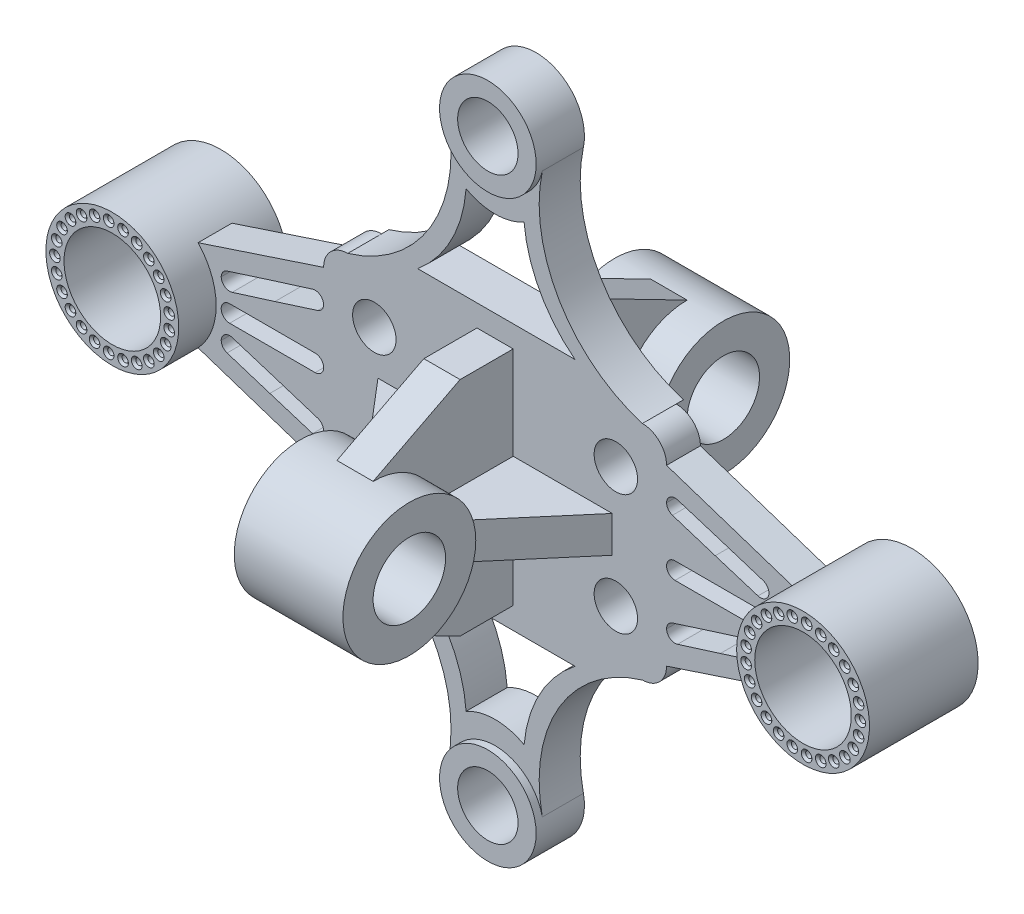
SolidWorks part; units mm, degrees
ref_plane "Front Plane" through (0, 0, 0) normal (1, 0, 0) x (0, 1, 0)
ref_plane "Top Plane" through (0, 0, 0) normal (0, 0, 1) x (0, 1, 0)
ref_plane "Right Plane" through (0, 0, 0) normal (0, 1, 0) x (-1, 0, 0)
sketch "Sketch1" plane through (0, 0, 0) normal (0, 0, 1) x (0, 1, 0)
  line L5 (-46, 71) -> (46, 71)
  line L6 (-46, 71) -> (-46, -71)
  line L7 (-46, -71) -> (46, -71)
  line L8 (46, 71) -> (46, -71)
  line L9 (-46, 71) -> (46, -71) construction
  line L10 (-46, -71) -> (46, 71) construction
  circle A1 centre (-25, -50) radius 9
  circle A2 centre (-25, 50) radius 9
  circle A3 centre (25, 50) radius 9
  circle A4 centre (25, -50) radius 9
  point P0 (0, 0)
  dimension "D5" = 18
  dimension "D1" = 92
  dimension "D2" = 142
  dimension "D3" = 21
  dimension "D4" = 21
  dimension "D6" = 2
  dimension "D7" = 2
extrude "Boss-Extrude1" add sketch "Sketch1" along normal blind 14
fillet "Fillet1" radius 10 4 edges at (-71, -46, 7) (-71, 46, 7) (71, 46, 7) (71, -46, 7)
sketch "Sketch2" plane through (0, 0, 0) normal (1, 0, 0) x (0, 1, 0)
  line L0 (-36, 0) -> (36, 0) construction
  circle A0 centre (0, 72) radius 27.5
  arc A1 (-27.5, 72) -> (27.5, 72) centre (0, 72) ccw
  point P6 (0, 0)
  point P7 (0, 0)
  dimension "D2" = 55
  dimension "D1" = 72
extrude "Boss-Extrude2" add sketch "Sketch2" along normal blind 22.5 and the other way blind 22.5 separate body contours A0
sketch "Sketch7" plane through (0, 0, 0) normal (1, 0, 0) x (0, 1, 0)
  line L0 (-46, 14) -> (-46, 36)
  line L1 (-36, 14) -> (-46, 14) construction
  line L2 (-46, 36) -> (-27.5, 72)
  line L3 (46, 14) -> (46, 36)
  line L4 (46, 36) -> (27.5, 72)
  line L5 (-46, 14) -> (46, 14)
  arc A0 (-27.5, 72) -> (27.5, 72) centre (0, 74.4278) ccw
  dimension "D2" = 27.607
  dimension "D1" = 22
extrude "Boss-Extrude3" add sketch "Sketch7" along normal blind 7.5 and the other way blind 7.5
sketch "Sketch8" plane through (0, 0, 0) normal (0, 1, 0) x (-1, 0, 0)
  line L0 (-22.5, 44.5) -> (-48.5, 14)
  line L1 (-61, 14) -> (-7.5, 14) construction
  dimension "D1" = 41
rib "Rib32" sketch "Sketch8" sketch "Sketch8" thickness 15 extrusion direction parallel to sketch draft on no parameters "D1"=15
mirror "Mirror1" about plane through (0, 0, 0) normal (1, 0, 0) of "Rib32"
sketch "Sketch9" plane through (22.5, 0, 0) normal (1, 0, 0) x (0, 1, 0)
  circle A0 centre (0, 72) radius 15
  dimension "D1" = 30
extrude "Cut-Extrude1" cut sketch "Sketch9" against normal through all
ref_plane "Plane1" through (0, 0, 7) normal (0, 0, 1) x (0, 1, 0)
mirror "Mirror3" about plane through (0, 0, 7) normal (0, 0, 1) of bodies 105
ref_plane "Plane3" through (0, 0, 7) normal (0, 0, 1) x (0, 1, 0)
sketch "Sketch11" plane through (0, 0, 7) normal (0, 0, 1) x (0, 1, 0)
  line L0 (36, 71) -> (-36, 71) construction
  line L1 (36, 71) -> (-36, 71)
  circle A0 centre (0, 143) radius 27.5
  circle A1 centre (0, 143) radius 20
  point P8 (0, 71)
  dimension "D2" = 55
  dimension "D3" = 40
  dimension "D1" = 72
extrude "Boss-Extrude4" add sketch "Sketch11" along normal blind 22.5 and the other way blind 22.5 separate body contours A0 | A1
sketch "Sketch12" plane through (0, 0, 7) normal (0, 0, 1) x (0, 1, 0)
  line L0 (-18.8482, 122.9751) -> (-36, 71)
  line L1 (36, 71) -> (18.8482, 122.9751)
  line L2 (36, 71) -> (-36, 71)
  circle A0 centre (0, 143) radius 27.5 construction
  arc A1 (18.8482, 122.9751) -> (-18.8482, 122.9751) centre (0, 143) cw
  dimension "D1" = 54.7321
extrude "Boss-Extrude5" add sketch "Sketch12" along normal blind 7 and the other way blind 7
hole_wizard "CSK for M2 Flat Head Machine Screw2" positions "Sketch17" profile "Sketch16" countersink size "M2" standard "ANSI Metric" end condition through all
sketch "Sketch17" plane through (0, 0, 29.5) normal (0, 0, 1) x (1, 0, 0)
  circle A0 centre (-143, 0) radius 27.5 construction
  point P0 (-166.75, 0)
  point P3 (0, 0)
  point P6 (0, 0)
  point P7 (0, 0)
  point P12 (-145.251, 5.2276)
  point P17 (-143.3311, -0.3544)
  dimension "D1" = 23.75
sketch "Sketch16" plane through (-166.75, 0, 29.5) normal (1, 0, 0) x (0, -1, 0)
  line L0 (0, 0) -> (0, 115)
  line L1 (0, 115) -> (1.3, 115)
  line L2 (1.3, 115) -> (1.3, 0.9)
  line L3 (1.3, 0.9) -> (2.2, 0)
  line L5 (2.2, 0) -> (0, 0)
  line L6 (-1.3, 0.9) -> (-2.2, 0) construction
  line L11 (0, -6.35) -> (0, 107.95) construction
  dimension "Thru Hole Dia." = 2.6
  dimension "Thru Hole Depth" = 115
  dimension "Near C'Sink Dia." = 4.4
  dimension "Near C'Sink Angle" = 90
pattern_circular "CirPattern1" count 25 over 360 about axis through (-143, 0, 0) along (0, 0, 1) of "CSK for M2 Flat Head Machine Screw2"
sketch "Sketch18" plane through (0, 0, 14) normal (0, 0, 1) x (1, 0, 0)
  line L0 (-109.9084, 11.449) -> (-74.5, 22.551) construction
  line L1 (-110.9555, 14.7887) -> (-75.5471, 25.8906)
  line L2 (-108.8613, 8.1094) -> (-73.4529, 19.2113)
  line L3 (-109.9084, -11.3544) -> (-74.5, -22.6456) construction
  line L4 (-108.845, -8.0198) -> (-73.4367, -19.311)
  line L5 (-110.9717, -14.689) -> (-75.5633, -25.9802)
  line L6 (-109.9084, 0) -> (-74.5, 0) construction
  line L7 (-109.9084, 3.5) -> (-74.5, 3.5)
  line L8 (-71, 36) -> (-71, -36) construction
  line L9 (-71, 36) -> (-122.9751, 18.8482) construction
  line L10 (-163, 0) -> (-123, 0) construction
  line L11 (-109.9084, -3.5) -> (-74.5, -3.5)
  arc A0 (-110.9555, 14.7887) -> (-108.8613, 8.1094) centre (-109.9084, 11.449) ccw
  arc A1 (-73.4529, 19.2113) -> (-75.5471, 25.8906) centre (-74.5, 22.551) ccw
  arc A2 (-108.845, -8.0198) -> (-110.9717, -14.689) centre (-109.9084, -11.3544) ccw
  arc A3 (-75.5633, -25.9802) -> (-73.4367, -19.311) centre (-74.5, -22.6456) ccw
  circle A4 centre (-143, 0) radius 20 construction
  arc A5 (-109.9084, 3.5) -> (-109.9084, -3.5) centre (-109.9084, 0) ccw
  arc A6 (-74.5, -3.5) -> (-74.5, 3.5) centre (-74.5, 0) ccw
  point P2 (-92.2042, 17)
  point P7 (-92.2042, -17)
  point P23 (0, 0)
  point P24 (0, 0)
  point P26 (-92.2042, 0)
  point P33 (-106.0535, 3.8263)
  point P34 (-73.4529, 8.8994)
  point P35 (0, 0)
  point P36 (0, 0)
  point P37 (0, 0)
  point P38 (0, 0)
  point P39 (0, 0)
  point P40 (0, 0)
  point P41 (0, 0)
  dimension "D1" = 3.5
  dimension "D2" = 3.5
  dimension "D4" = 3.5
  dimension "D9" = 3.5
  dimension "D3" = 35.4084
  dimension "D5" = 17
  dimension "D6" = 17
  dimension "D7" = 11.449
  dimension "D8" = 11.3544
extrude "Cut-Extrude2" cut sketch "Sketch18" against normal through all
mirror "Mirror13" about plane through (0, 0, 0) normal (1, 0, 0) of bodies 112
sketch "Sketch19" plane through (0, 0, 7) normal (0, 0, 1) x (0, 1, 0)
  line L0 (46, 0) -> (120, 0) construction
  line L1 (46, 7.5) -> (46, -7.5) construction
  circle A0 centre (120, 0) radius 20
  circle A1 centre (120, 0) radius 12.5
  dimension "D1" = 40
  dimension "D2" = 25
  dimension "D3" = 120
extrude "Boss-Extrude6" add sketch "Sketch19" along normal blind 10 and the other way blind 10 separate body
sketch "Sketch20" plane through (0, 0, 7) normal (0, 0, 1) x (0, 1, 0)
  line L0 (46, 61) -> (46, -61)
  line L2 (55, 32.0735) -> (55, -33.0883)
  line L3 (46, 0) -> (120, 0) construction
  arc A0 (115.8245, 19.5593) -> (46, 61) centre (103.3354, 78.061) cw
  circle A1 centre (120, 0) radius 20 construction
  arc A2 (115.8245, -19.5593) -> (46, -61) centre (103.3354, -78.061) ccw
  arc A3 (115.8245, -19.5593) -> (115.8245, 19.5593) centre (120, 0) cw
  arc A4 (115.8245, 19.5593) -> (115.8245, -19.5593) centre (120, 0) ccw
  arc A8 (55, 32.0735) -> (93.6914, 12) centre (97.8693, 67.3783) ccw
  arc A10 (55, -33.0883) -> (93.6914, -12) centre (98.5959, -67.0367) cw
  arc A11 (93.6914, 12) -> (93.6914, -12) centre (115.4112, 0) ccw
  dimension "D1" = 9
  dimension "Diam" = 59.82
  dimension "D3" = 12
  dimension "D4" = 33.0883
  dimension "D2" = 12
  dimension "D5" = 12
  dimension "D6" = 12
extrude "Boss-Extrude7" add sketch "Sketch20" along normal blind 7 and the other way blind 10 contours A2 A3 A0 L0 | L0 L3 L2 A8 A11 A4 A0
mirror "Mirror14" about plane through (0, 0, 0) normal (0, 1, 0) of bodies 117
equation "\"Diam\"=59.82"
